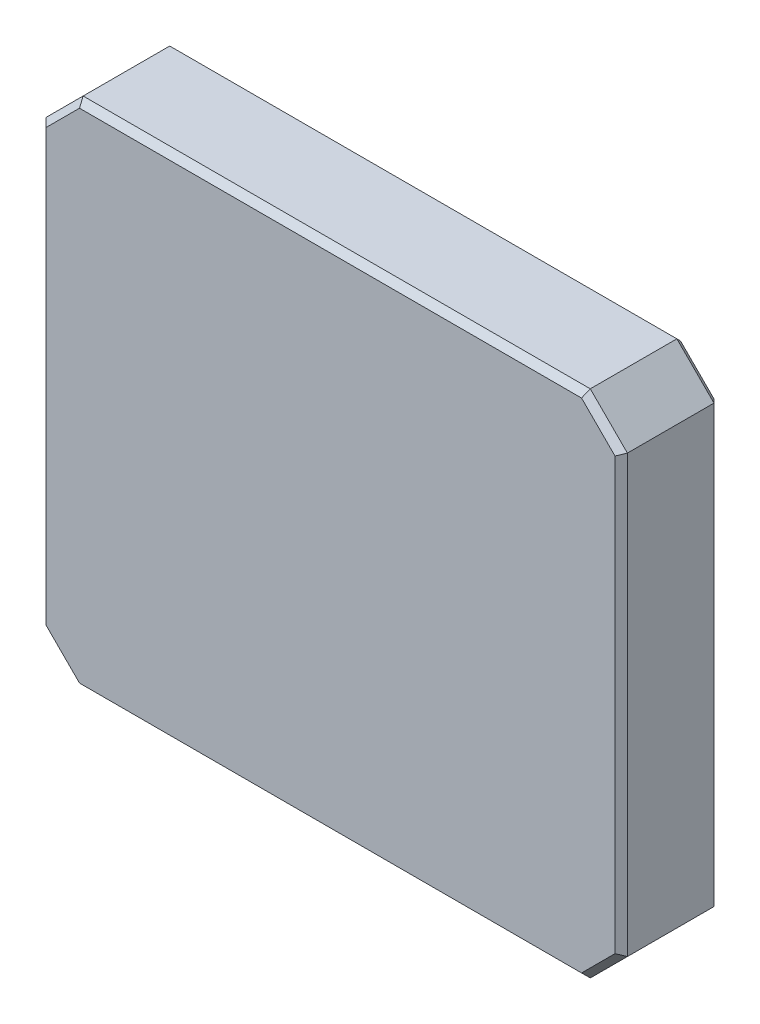
SolidWorks part; units mm, degrees
ref_plane "Front Plane" through (0, 0, 0) normal (0, 0, 1) x (1, 0, 0)
ref_plane "Top Plane" through (0, 0, 0) normal (0, 1, 0) x (1, 0, 0)
ref_plane "Right Plane" through (0, 0, 0) normal (1, 0, 0) x (0, 0, -1)
sketch "Sketch1" plane through (0, 0, 0) normal (0, 0, 1) x (1, 0, 0)
  line L0 (-47, 35.25) -> (-41, 41.25)
  line L1 (-41, -41.25) -> (41, -41.25)
  line L2 (-47, -35.25) -> (-47, 35.25)
  line L3 (-41, 41.25) -> (41, 41.25)
  line L4 (47, -35.25) -> (47, 35.25)
  line L5 (-47, -41.25) -> (47, 41.25) construction
  line L6 (-47, 41.25) -> (47, -41.25) construction
  line L7 (41, 41.25) -> (47, 35.25)
  line L8 (41, -41.25) -> (47, -35.25)
  line L9 (-47, -35.25) -> (-41, -41.25)
  point P0 (0, 0)
  dimension "D1" = 94
  dimension "D2" = 82.5
extrude "Boss-Extrude1" add sketch "Sketch1" along normal blind 16
chamfer "Chamfer1" distance 1 16 edges at (-44, 38.25, 16) (0, 41.25, 16) (44, 38.25, 16) (47, 0, 16) (44, -38.25, 16) (0, -41.25, 16) (-44, -38.25, 16) (-47, 0, 16) (-44, 38.25, 0) (0, 41.25, 0) (44, 38.25, 0) (47, 0, 0) (44, -38.25, 0) (0, -41.25, 0) (-44, -38.25, 0) (-47, 0, 0)
